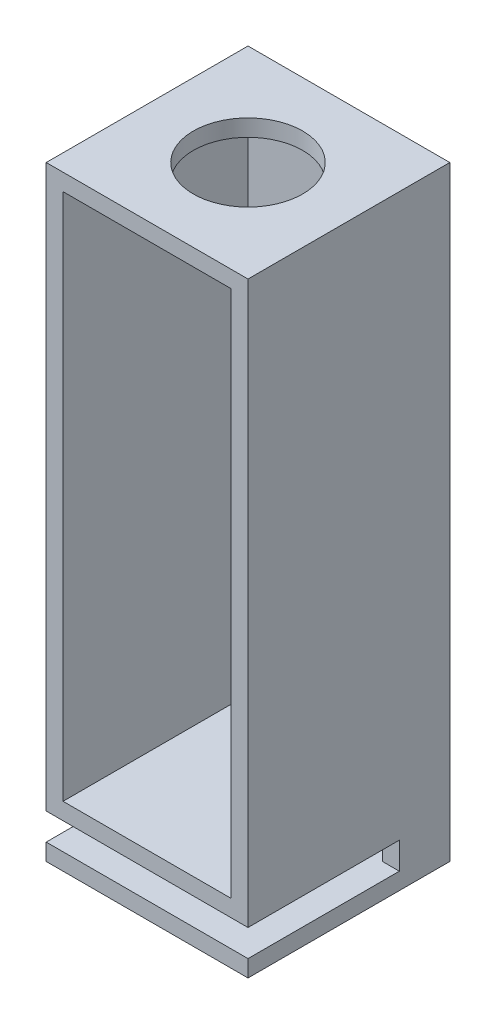
SolidWorks part; units mm, degrees
ref_plane "Alzado" through (0, 0, 0) normal (0, 0, 1) x (1, 0, 0)
ref_plane "Planta" through (0, 0, 0) normal (0, 1, 0) x (1, 0, 0)
ref_plane "Vista lateral" through (0, 0, 0) normal (1, 0, 0) x (0, 0, -1)
sketch "Croquis1" plane through (0, 0, 0) normal (0, 1, 0) x (1, 0, 0)
  line L1 (-6, 6) -> (6, 6)
  line L2 (-6, 6) -> (-6, -6)
  line L3 (-6, -6) -> (6, -6)
  line L4 (6, 6) -> (6, -6)
  line L5 (-6, 6) -> (6, -6) construction
  line L6 (-6, -6) -> (6, 6) construction
  point P0 (0, 0)
  dimension "D1" = 12
  dimension "D2" = 12
extrude "Saliente-Extruir1" add sketch "Croquis1" along normal blind 36
shell "Vaciado1" thickness 1
sketch "Croquis2" plane through (0, 36, 0) normal (0, 1, 0) x (1, 0, 0)
  circle A0 centre (0, 0) radius 3.25
  dimension "D1" = 6.5
extrude "Cortar-Extruir1" cut sketch "Croquis2" against normal blind 3 and the other way through all
sketch "Croquis3" plane through (0, 0, 6) normal (0, 0, 1) x (1, 0, 0)
  line L1 (-6.7727, 1) -> (6.8802, 1)
  line L2 (-6.7727, 1) -> (-6.7727, 2.6)
  line L3 (-6.7727, 2.6) -> (6.8802, 2.6)
  line L4 (6.8802, 1) -> (6.8802, 2.6)
  line L5 (-6, 0) -> (6, 0) construction
  dimension "D1" = 1.6
  dimension "D2" = 1
extrude "Cortar-Extruir2" cut sketch "Croquis3" against normal blind 9
sketch "Croquis4" plane through (0, 0, 6) normal (0, 0, 1) x (1, 0, 0)
  line L0 (5, 35) -> (5, 2.6) construction
  line L1 (-5, 2.6) -> (5, 2.6)
  line L2 (-5, 2.6) -> (-5, 3.6)
  line L3 (-5, 3.6) -> (5, 3.6)
  line L4 (5, 2.6) -> (5, 3.6)
  dimension "D1" = 1
extrude "Saliente-Extruir2" add sketch "Croquis4" against normal up to surface (11 mm away) up to face at (0, 18, -5)
